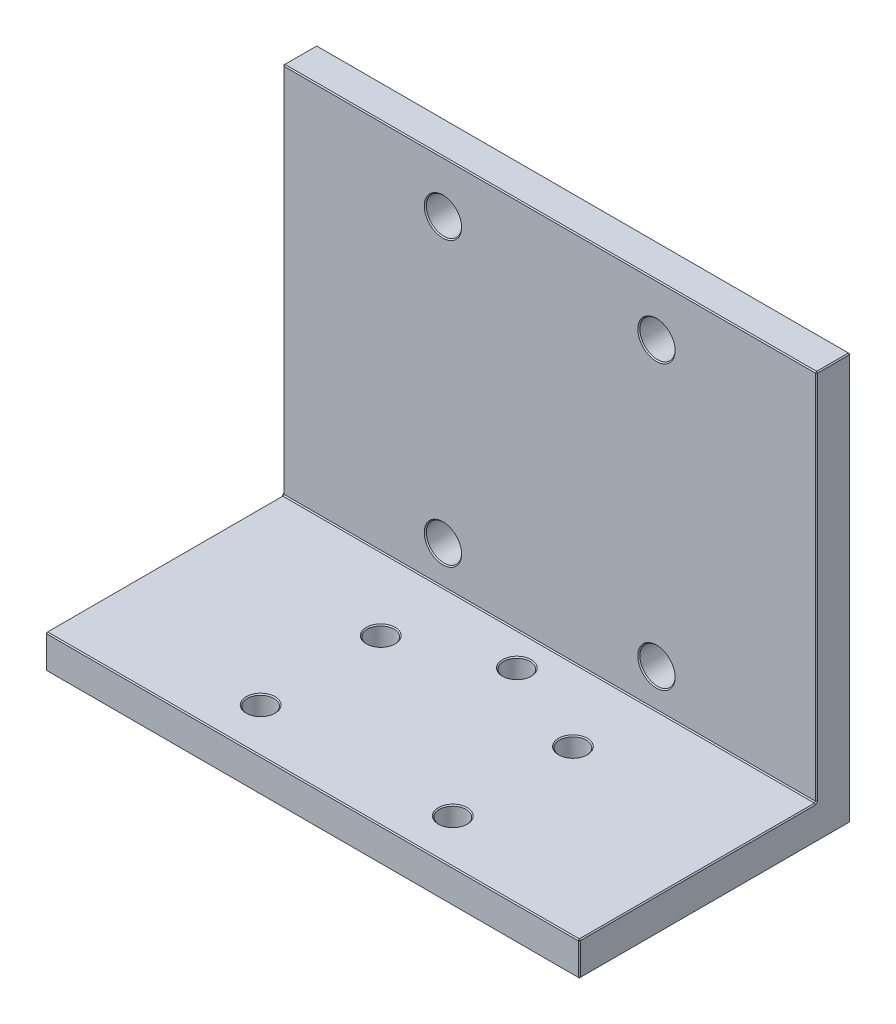
SolidWorks part; units mm, degrees
ref_plane "Front Plane" through (0, 0, 0) normal (0, 0, 1) x (1, 0, 0)
ref_plane "Top Plane" through (0, 0, 0) normal (0, 1, 0) x (1, 0, 0)
ref_plane "Right Plane" through (0, 0, 0) normal (1, 0, 0) x (0, 0, -1)
sketch "Sketch1" plane through (0, 0, 0) normal (1, 0, 0) x (0, 0, -1)
  line L2 (0, 0) -> (0, 76.2)
  line L3 (0, 76.2) -> (-6.35, 76.2)
  line L4 (-6.35, 6.35) -> (-6.35, 76.2)
  line L5 (0, 0) -> (-50.8, 0)
  line L7 (-6.35, 6.35) -> (-50.8, 6.35)
  line L8 (-50.8, 0) -> (-50.8, 6.35)
  dimension "D1" = 6.35
  dimension "D2" = 76.2
  dimension "D3" = 50.8
extrude "Boss-Extrude1" add sketch "Sketch1" along normal mid plane 100
sketch "Sketch2" plane through (0, 0, 6.35) normal (0, 0, 1) x (1, 0, 0)
  line L0 (0, 40) -> (0, 0) construction
  line L1 (20, 13.5) -> (-20, 13.5) construction
  line L2 (20, 13.5) -> (20, 66.5) construction
  line L3 (20, 66.5) -> (-20, 66.5) construction
  line L4 (-20, 13.5) -> (-20, 66.5) construction
  line L5 (20, 13.5) -> (-20, 66.5) construction
  line L6 (20, 66.5) -> (-20, 13.5) construction
  line L7 (50, 76.2) -> (-50, 76.2) construction
  circle A0 centre (-20, 66.5) radius 3.3
  circle A1 centre (20, 66.5) radius 3.3
  circle A2 centre (20, 13.5) radius 3.3
  circle A3 centre (-20, 13.5) radius 3.3
  point P0 (0, 40)
  dimension "D1" = 6.6
  dimension "D2" = 40
  dimension "D3" = 53
  dimension "D4" = 9.7
extrude "Cut-Extrude1" cut sketch "Sketch2" against normal blind 100
sketch "Sketch3" plane through (0, 6.35, 0) normal (0, 1, 0) x (1, 0, 0)
  line L0 (0, 0) -> (0, -31.25) construction
  line L1 (18, -20) -> (-18, -20) construction
  line L2 (18, -20) -> (18, -42.5) construction
  line L3 (18, -42.5) -> (-18, -42.5) construction
  line L4 (-18, -20) -> (-18, -42.5) construction
  line L5 (18, -20) -> (-18, -42.5) construction
  line L6 (18, -42.5) -> (-18, -20) construction
  line L7 (50, 0) -> (-50, 0) construction
  line L8 (50, -50.8) -> (-50, -50.8) construction
  circle A0 centre (-18, -20) radius 2.5
  circle A1 centre (-18, -42.5) radius 2.5
  circle A2 centre (18, -42.5) radius 2.5
  circle A3 centre (18, -20) radius 2.5
  circle A4 centre (0, -12.5) radius 2.5
  point P0 (0, -31.25)
  dimension "D1" = 5
  dimension "D2" = 22.5
  dimension "D3" = 36
  dimension "D4" = 12.5
  dimension "D5" = 8.3
extrude "Cut-Extrude2" cut sketch "Sketch3" against normal blind 100
chamfer "Chamfer1" distance 0.2 angle 45 36 edges at (-18, 6.35, 22.5) (-18, 6.35, 45) (18, 6.35, 45) (18, 6.35, 22.5) (0, 6.35, 15) (-16.7, 66.5, 6.35) (23.3, 66.5, 6.35) (23.3, 13.5, 6.35) (-16.7, 13.5, 6.35) (50, 6.35, 28.575) (0, 6.35, 50.8) (-50, 6.35, 28.575) (0, 76.2, 6.35) (50, 41.275, 6.35) (0, 6.35, 6.35) (-50, 41.275, 6.35) (0, 0, 0) (0, 76.2, 0) (50, 3.175, 50.8) (50, 76.2, 3.175) (50, 38.1, 0) (50, 0, 25.4) (0, 0, 50.8) (-50, 3.175, 50.8) (-50, 76.2, 3.175) (-50, 38.1, 0) (-50, 0, 25.4) (-16.7, 66.5, 0) (23.3, 66.5, 0) (23.3, 13.5, 0) (-16.7, 13.5, 0) (-18, 0, 22.5) (-18, 0, 45) (18, 0, 45) (18, 0, 22.5) (0, 0, 15)
equation "\"M5_tap\"=4.2mm"
equation "\"M5_clearence\"=5.5mm"
equation "\"M6_tap\"=5mm"
equation "\"M6_clearence\"=6.6mm"
equation "\"D1@Sketch2\"=\"M6_clearence\""
equation "\"D1@Sketch3\"=\"M6_tap\""
